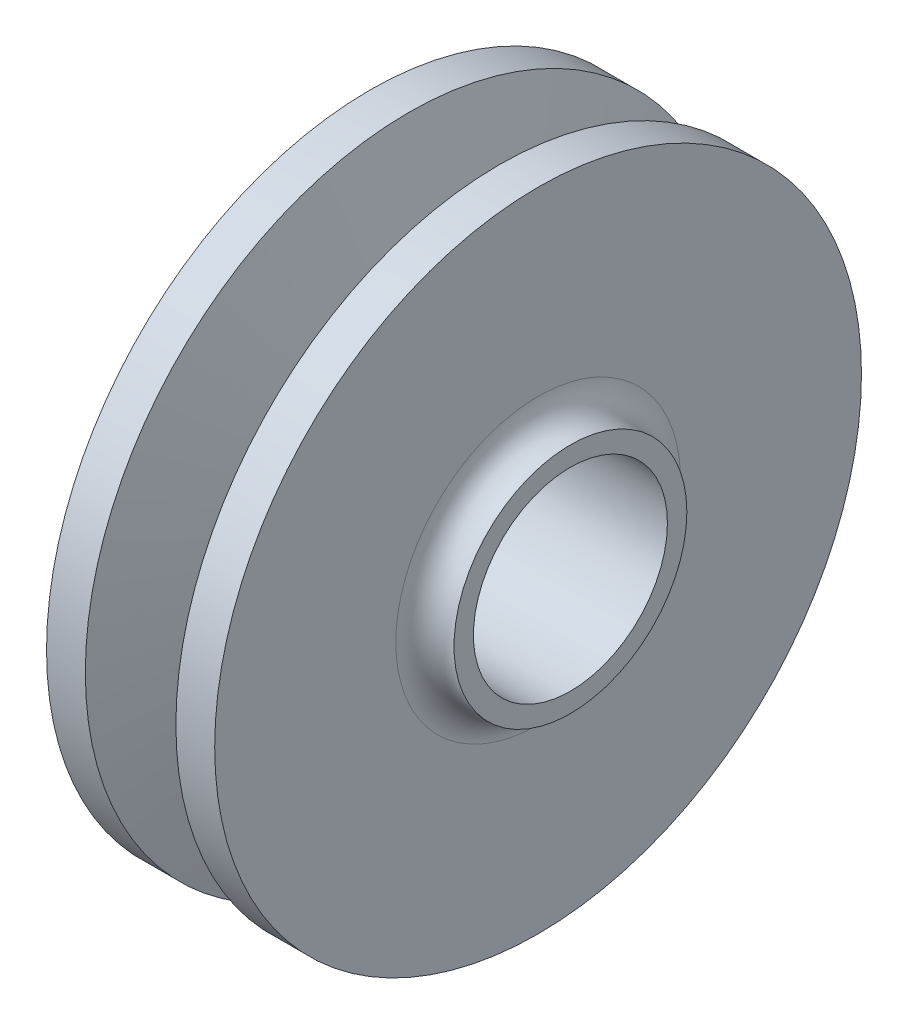
SolidWorks part; units mm, degrees
ref_plane "Front Plane" through (0, 0, 0) normal (0, 0, 1) x (1, 0, 0)
ref_plane "Top Plane" through (0, 0, 0) normal (0, 1, 0) x (1, 0, 0)
ref_plane "Right Plane" through (0, 0, 0) normal (1, 0, 0) x (0, 0, -1)
sketch "Sketch1" plane through (0, 0, 0) normal (0, 0, 1) x (1, 0, 0)
  line L0 (18, 15) -> (-18, 15)
  line L1 (0, 0) -> (0, 58.8182) construction
  line L2 (18, 15) -> (18, 18)
  line L3 (-18, 15) -> (-18, 18)
  line L4 (3, 35) -> (-3, 35)
  line L5 (7, 50) -> (13, 50)
  line L6 (7, 50) -> (3, 35)
  line L7 (13, 50) -> (13, 22)
  line L8 (-13, 50) -> (-13, 22)
  line L9 (-7, 50) -> (-3, 35)
  line L10 (-7, 50) -> (-13, 50)
  line L11 (38.2299, 0) -> (-40.7766, 0) construction
  arc A0 (18, 18) -> (13, 22) centre (17.1, 22) cw
  arc A1 (-18, 18) -> (-13, 22) centre (-17.1, 22) ccw
  dimension "D1" = 15
  dimension "D3" = 36
  dimension "D4" = 3
  dimension "D5" = 3
  dimension "D7" = 20
  dimension "D8" = 7
  dimension "D9" = 6
  dimension "D10" = 15
  dimension "D11" = 28
revolve "Revolve1" add sketch "Sketch1" angle 360 about L11
